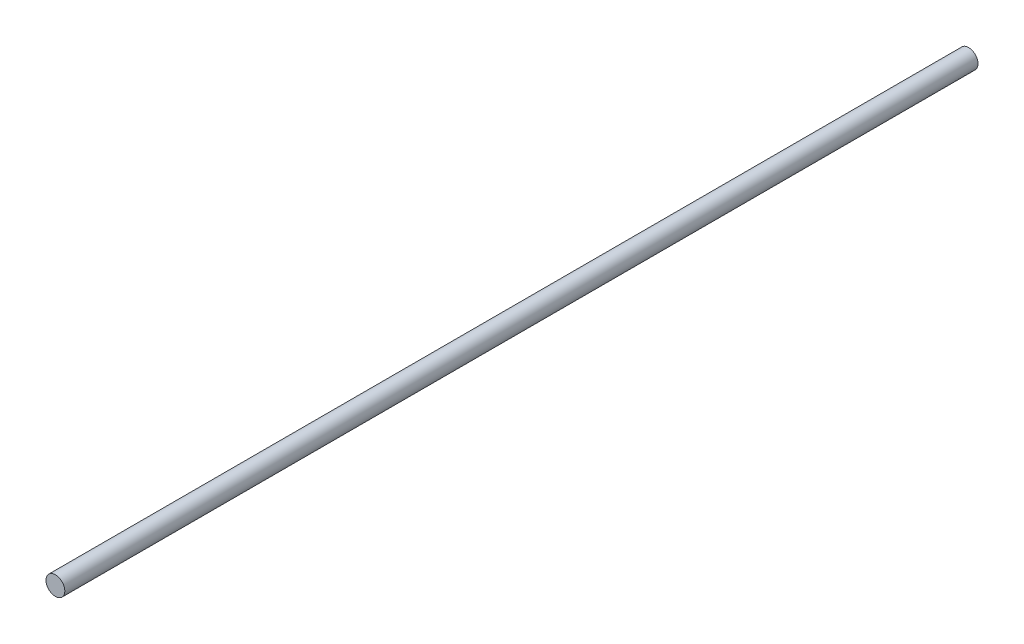
SolidWorks part; units mm, degrees
ref_plane "Front Plane" through (0, 0, 0) normal (0, 0, 1) x (1, 0, 0)
ref_plane "Top Plane" through (0, 0, 0) normal (0, 1, 0) x (1, 0, 0)
ref_plane "Right Plane" through (0, 0, 0) normal (1, 0, 0) x (0, 0, -1)
sketch "Sketch1" plane through (0, 0, 0) normal (0, 0, 1) x (1, 0, 0)
  circle A1 centre (20, 0) radius 1
extrude "Boss-Extrude1" add sketch "Sketch1" against normal blind 97
